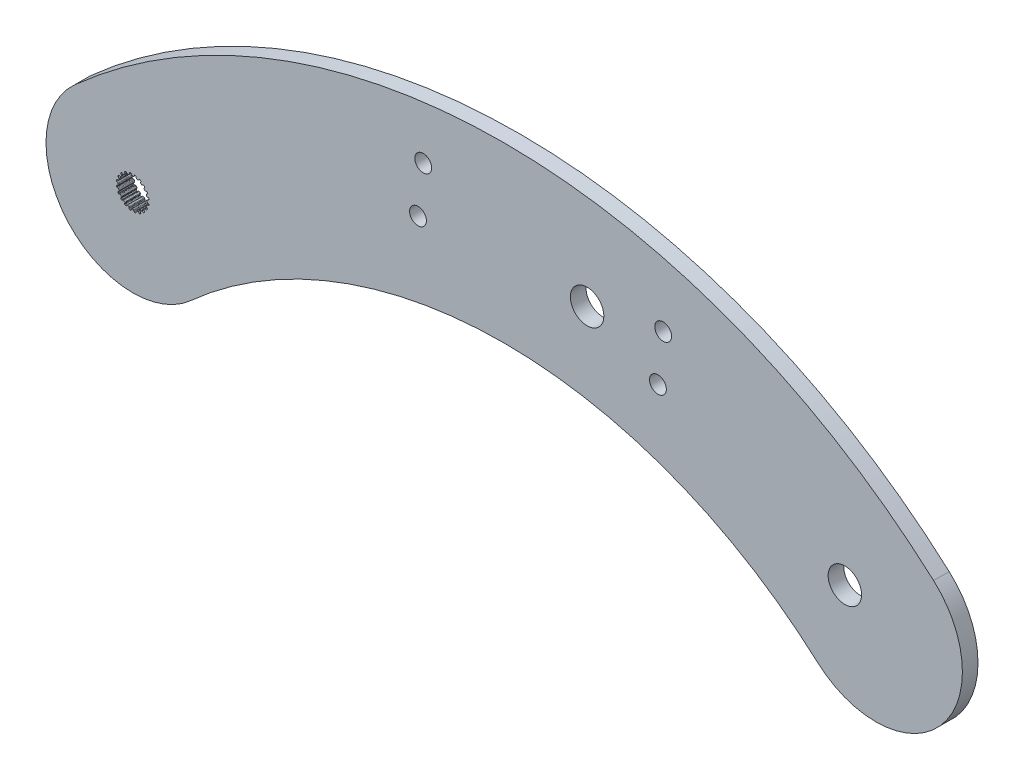
SolidWorks part; units mm, degrees
ref_plane "Front Plane" through (0, 0, 0) normal (0, 0, 1) x (1, 0, 0)
ref_plane "Top Plane" through (0, 0, 0) normal (0, 1, 0) x (1, 0, 0)
ref_plane "Right Plane" through (0, 0, 0) normal (1, 0, 0) x (0, 0, -1)
sketch "Sketch1" plane through (0, 0, 0) normal (0, 0, 1) x (1, 0, 0)
  line L0 (-0.1069, 2.9699) -> (0.1069, 2.9699)
  line L1 (0.3159, 3.2375) -> (0.2537, 3.0575)
  line L2 (-0.2964, 3.2367) -> (-0.2318, 3.0575)
  line L3 (-0.2964, 3.2367) -> (0.3159, 3.2375) construction
  line L4 (0, 3.3252) -> (0, 0) construction
  line L5 (-0.2318, 3.0575) -> (0.2537, 3.0575) construction
  line L6 (-0.4281, 3.3241) -> (0.4281, 3.3263) construction
  line L7 (0.7183, 3.1698) -> (0.7244, 2.9795)
  line L8 (0.816, 2.8576) -> (1.0195, 2.7915)
  line L9 (1.3009, 2.9815) -> (1.1862, 2.8295)
  line L10 (1.6627, 2.7927) -> (1.6097, 2.6099)
  line L11 (1.6591, 2.4655) -> (1.8322, 2.3398)
  line L12 (2.1585, 2.4335) -> (2.0025, 2.3245)
  line L13 (2.4443, 2.1423) -> (2.3374, 1.9847)
  line L14 (2.3398, 1.8322) -> (2.4655, 1.6591)
  line L15 (2.8049, 1.6474) -> (2.6228, 1.5919)
  line L16 (2.9866, 1.2821) -> (2.8363, 1.1653)
  line L17 (2.7915, 1.0195) -> (2.8576, 0.816)
  line L18 (3.1767, 0.7) -> (2.9863, 0.7035)
  line L19 (3.2367, 0.2964) -> (3.0575, 0.2318)
  line L20 (2.9699, 0.1069) -> (2.9699, -0.1069)
  line L21 (3.2375, -0.3159) -> (3.0575, -0.2537)
  line L22 (3.1698, -0.7183) -> (2.9795, -0.7244)
  line L23 (2.8576, -0.816) -> (2.7915, -1.0195)
  line L24 (2.9815, -1.3009) -> (2.8295, -1.1862)
  line L25 (2.7927, -1.6627) -> (2.6099, -1.6097)
  line L26 (2.4655, -1.6591) -> (2.3398, -1.8322)
  line L27 (2.4335, -2.1585) -> (2.3245, -2.0025)
  line L28 (2.1423, -2.4443) -> (1.9847, -2.3374)
  line L29 (1.8322, -2.3398) -> (1.6591, -2.4655)
  line L30 (1.6474, -2.8049) -> (1.5919, -2.6228)
  line L31 (1.2821, -2.9866) -> (1.1653, -2.8363)
  line L32 (1.0195, -2.7915) -> (0.816, -2.8576)
  line L33 (0.7, -3.1767) -> (0.7035, -2.9863)
  line L34 (0.2964, -3.2367) -> (0.2318, -3.0575)
  line L35 (0.1069, -2.9699) -> (-0.1069, -2.9699)
  line L36 (-0.3159, -3.2375) -> (-0.2537, -3.0575)
  line L37 (-0.7183, -3.1698) -> (-0.7244, -2.9795)
  line L38 (-0.816, -2.8576) -> (-1.0195, -2.7915)
  line L39 (-1.3009, -2.9815) -> (-1.1862, -2.8295)
  line L40 (-1.6627, -2.7927) -> (-1.6097, -2.6099)
  line L41 (-1.6591, -2.4655) -> (-1.8322, -2.3398)
  line L42 (-2.1585, -2.4335) -> (-2.0025, -2.3245)
  line L43 (-2.4443, -2.1423) -> (-2.3374, -1.9847)
  line L44 (-2.3398, -1.8322) -> (-2.4655, -1.6591)
  line L45 (-2.8049, -1.6474) -> (-2.6228, -1.5919)
  line L46 (-2.9866, -1.2821) -> (-2.8363, -1.1653)
  line L47 (-2.7915, -1.0195) -> (-2.8576, -0.816)
  line L48 (-3.1767, -0.7) -> (-2.9863, -0.7035)
  line L49 (-3.2367, -0.2964) -> (-3.0575, -0.2318)
  line L50 (-2.9699, -0.1069) -> (-2.9699, 0.1069)
  line L51 (-3.2375, 0.3159) -> (-3.0575, 0.2537)
  line L52 (-3.1698, 0.7183) -> (-2.9795, 0.7244)
  line L53 (-2.8576, 0.816) -> (-2.7915, 1.0195)
  line L54 (-2.9815, 1.3009) -> (-2.8295, 1.1862)
  line L55 (-2.7927, 1.6627) -> (-2.6099, 1.6097)
  line L56 (-2.4655, 1.6591) -> (-2.3398, 1.8322)
  line L57 (-2.4335, 2.1585) -> (-2.3245, 2.0025)
  line L58 (-2.1423, 2.4443) -> (-1.9847, 2.3374)
  line L59 (-1.8322, 2.3398) -> (-1.6591, 2.4655)
  line L60 (-1.6474, 2.8049) -> (-1.5919, 2.6228)
  line L61 (-1.2821, 2.9866) -> (-1.1653, 2.8363)
  line L62 (-1.0195, 2.7915) -> (-0.816, 2.8576)
  line L63 (-0.7, 3.1767) -> (-0.7035, 2.9863)
  line L64 (0.4281, 3.3263) -> (0.62, 3.2938)
  line L65 (1.4351, 3.0312) -> (1.6075, 2.9409)
  line L66 (2.3015, 2.4394) -> (2.4376, 2.3003)
  line L67 (2.9427, 1.6088) -> (3.0291, 1.4344)
  line L68 (3.2958, 0.6207) -> (3.3241, 0.4281)
  line L69 (3.3263, -0.4281) -> (3.2938, -0.62)
  line L70 (3.0312, -1.4351) -> (2.9409, -1.6075)
  line L71 (2.4394, -2.3015) -> (2.3003, -2.4376)
  line L72 (1.6088, -2.9427) -> (1.4344, -3.0291)
  line L73 (0.6207, -3.2958) -> (0.4281, -3.3241)
  line L74 (-0.4281, -3.3263) -> (-0.62, -3.2938)
  line L75 (-1.4351, -3.0312) -> (-1.6075, -2.9409)
  line L76 (-2.3015, -2.4394) -> (-2.4376, -2.3003)
  line L77 (-2.9427, -1.6088) -> (-3.0291, -1.4344)
  line L78 (-3.2958, -0.6207) -> (-3.3241, -0.4281)
  line L79 (-3.3263, 0.4281) -> (-3.2938, 0.62)
  line L80 (-3.0312, 1.4351) -> (-2.9409, 1.6075)
  line L81 (-2.4394, 2.3015) -> (-2.3003, 2.4376)
  line L82 (-1.6088, 2.9427) -> (-1.4344, 3.0291)
  line L83 (-0.6207, 3.2958) -> (-0.4281, 3.3241)
  line L84 (-11.8753, 13.2369) -> (11.8753, -13.2369) construction
  line L85 (164.2753, 13.2369) -> (140.5247, -13.2369) construction
  line L86 (0, 0) -> (152.4, 0) construction
  arc A0 (0.2537, 3.0575) -> (0.1069, 2.9699) centre (0.1283, 3.1009) cw
  arc A1 (-0.2318, 3.0575) -> (-0.1069, 2.9699) centre (-0.1069, 3.1026) ccw
  arc A2 (0.62, 3.2938) -> (0.7183, 3.1698) centre (0.5856, 3.1656) cw
  arc A3 (0.7244, 2.9795) -> (0.816, 2.8576) centre (0.857, 2.9838) ccw
  arc A4 (-0.4281, 3.3241) -> (-0.2964, 3.2367) centre (-0.4213, 3.1916) cw
  arc A5 (0.4281, 3.3263) -> (0.3159, 3.2375) centre (0.4413, 3.1942) ccw
  arc A6 (1.1862, 2.8295) -> (1.0195, 2.7915) centre (1.0802, 2.9095) cw
  arc A7 (1.4351, 3.0312) -> (1.3009, 2.9815) centre (1.4068, 2.9015) ccw
  arc A8 (1.6075, 2.9409) -> (1.6627, 2.7927) centre (1.5352, 2.8297) cw
  arc A9 (1.6097, 2.6099) -> (1.6591, 2.4655) centre (1.7371, 2.5729) ccw
  arc A10 (2.0025, 2.3245) -> (1.8322, 2.3398) centre (1.9264, 2.4332) cw
  arc A11 (2.3015, 2.4394) -> (2.1585, 2.4335) centre (2.2346, 2.3248) ccw
  arc A12 (2.4376, 2.3003) -> (2.4443, 2.1423) centre (2.3345, 2.2168) cw
  arc A13 (2.3374, 1.9847) -> (2.3398, 1.8322) centre (2.4472, 1.9102) ccw
  arc A14 (2.6228, 1.5919) -> (2.4655, 1.6591) centre (2.5841, 1.7189) cw
  arc A15 (2.9427, 1.6088) -> (2.8049, 1.6474) centre (2.8436, 1.5205) ccw
  arc A16 (3.0291, 1.4344) -> (2.9866, 1.2821) centre (2.9052, 1.3869) cw
  arc A17 (2.8363, 1.1653) -> (2.7915, 1.0195) centre (2.9177, 1.0605) ccw
  arc A18 (2.9863, 0.7035) -> (2.8576, 0.816) centre (2.9887, 0.8362) cw
  arc A19 (3.2958, 0.6207) -> (3.1767, 0.7) centre (3.1743, 0.5673) ccw
  arc A20 (3.3241, 0.4281) -> (3.2367, 0.2964) centre (3.1916, 0.4213) cw
  arc A21 (3.0575, 0.2318) -> (2.9699, 0.1069) centre (3.1026, 0.1069) ccw
  arc A22 (3.0575, -0.2537) -> (2.9699, -0.1069) centre (3.1009, -0.1283) cw
  arc A23 (3.3263, -0.4281) -> (3.2375, -0.3159) centre (3.1942, -0.4413) ccw
  arc A24 (3.2938, -0.62) -> (3.1698, -0.7183) centre (3.1656, -0.5856) cw
  arc A25 (2.9795, -0.7244) -> (2.8576, -0.816) centre (2.9838, -0.857) ccw
  arc A26 (2.8295, -1.1862) -> (2.7915, -1.0195) centre (2.9095, -1.0802) cw
  arc A27 (3.0312, -1.4351) -> (2.9815, -1.3009) centre (2.9015, -1.4068) ccw
  arc A28 (2.9409, -1.6075) -> (2.7927, -1.6627) centre (2.8297, -1.5352) cw
  arc A29 (2.6099, -1.6097) -> (2.4655, -1.6591) centre (2.5729, -1.7371) ccw
  arc A30 (2.3245, -2.0025) -> (2.3398, -1.8322) centre (2.4332, -1.9264) cw
  arc A31 (2.4394, -2.3015) -> (2.4335, -2.1585) centre (2.3248, -2.2346) ccw
  arc A32 (2.3003, -2.4376) -> (2.1423, -2.4443) centre (2.2168, -2.3345) cw
  arc A33 (1.9847, -2.3374) -> (1.8322, -2.3398) centre (1.9102, -2.4472) ccw
  arc A34 (1.5919, -2.6228) -> (1.6591, -2.4655) centre (1.7189, -2.5841) cw
  arc A35 (1.6088, -2.9427) -> (1.6474, -2.8049) centre (1.5205, -2.8436) ccw
  arc A36 (1.4344, -3.0291) -> (1.2821, -2.9866) centre (1.3869, -2.9052) cw
  arc A37 (1.1653, -2.8363) -> (1.0195, -2.7915) centre (1.0605, -2.9177) ccw
  arc A38 (0.7035, -2.9863) -> (0.816, -2.8576) centre (0.8362, -2.9887) cw
  arc A39 (0.6207, -3.2958) -> (0.7, -3.1767) centre (0.5673, -3.1743) ccw
  arc A40 (0.4281, -3.3241) -> (0.2964, -3.2367) centre (0.4213, -3.1916) cw
  arc A41 (0.2318, -3.0575) -> (0.1069, -2.9699) centre (0.1069, -3.1026) ccw
  arc A42 (-0.2537, -3.0575) -> (-0.1069, -2.9699) centre (-0.1283, -3.1009) cw
  arc A43 (-0.4281, -3.3263) -> (-0.3159, -3.2375) centre (-0.4413, -3.1942) ccw
  arc A44 (-0.62, -3.2938) -> (-0.7183, -3.1698) centre (-0.5856, -3.1656) cw
  arc A45 (-0.7244, -2.9795) -> (-0.816, -2.8576) centre (-0.857, -2.9838) ccw
  arc A46 (-1.1862, -2.8295) -> (-1.0195, -2.7915) centre (-1.0802, -2.9095) cw
  arc A47 (-1.4351, -3.0312) -> (-1.3009, -2.9815) centre (-1.4068, -2.9015) ccw
  arc A48 (-1.6075, -2.9409) -> (-1.6627, -2.7927) centre (-1.5352, -2.8297) cw
  arc A49 (-1.6097, -2.6099) -> (-1.6591, -2.4655) centre (-1.7371, -2.5729) ccw
  arc A50 (-2.0025, -2.3245) -> (-1.8322, -2.3398) centre (-1.9264, -2.4332) cw
  arc A51 (-2.3015, -2.4394) -> (-2.1585, -2.4335) centre (-2.2346, -2.3248) ccw
  arc A52 (-2.4376, -2.3003) -> (-2.4443, -2.1423) centre (-2.3345, -2.2168) cw
  arc A53 (-2.3374, -1.9847) -> (-2.3398, -1.8322) centre (-2.4472, -1.9102) ccw
  arc A54 (-2.6228, -1.5919) -> (-2.4655, -1.6591) centre (-2.5841, -1.7189) cw
  arc A55 (-2.9427, -1.6088) -> (-2.8049, -1.6474) centre (-2.8436, -1.5205) ccw
  arc A56 (-3.0291, -1.4344) -> (-2.9866, -1.2821) centre (-2.9052, -1.3869) cw
  arc A57 (-2.8363, -1.1653) -> (-2.7915, -1.0195) centre (-2.9177, -1.0605) ccw
  arc A58 (-2.9863, -0.7035) -> (-2.8576, -0.816) centre (-2.9887, -0.8362) cw
  arc A59 (-3.2958, -0.6207) -> (-3.1767, -0.7) centre (-3.1743, -0.5673) ccw
  arc A60 (-3.3241, -0.4281) -> (-3.2367, -0.2964) centre (-3.1916, -0.4213) cw
  arc A61 (-3.0575, -0.2318) -> (-2.9699, -0.1069) centre (-3.1026, -0.1069) ccw
  arc A62 (-3.0575, 0.2537) -> (-2.9699, 0.1069) centre (-3.1009, 0.1283) cw
  arc A63 (-3.3263, 0.4281) -> (-3.2375, 0.3159) centre (-3.1942, 0.4413) ccw
  arc A64 (-3.2938, 0.62) -> (-3.1698, 0.7183) centre (-3.1656, 0.5856) cw
  arc A65 (-2.9795, 0.7244) -> (-2.8576, 0.816) centre (-2.9838, 0.857) ccw
  arc A66 (-2.8295, 1.1862) -> (-2.7915, 1.0195) centre (-2.9095, 1.0802) cw
  arc A67 (-3.0312, 1.4351) -> (-2.9815, 1.3009) centre (-2.9015, 1.4068) ccw
  arc A68 (-2.9409, 1.6075) -> (-2.7927, 1.6627) centre (-2.8297, 1.5352) cw
  arc A69 (-2.6099, 1.6097) -> (-2.4655, 1.6591) centre (-2.5729, 1.7371) ccw
  arc A70 (-2.3245, 2.0025) -> (-2.3398, 1.8322) centre (-2.4332, 1.9264) cw
  arc A71 (-2.4394, 2.3015) -> (-2.4335, 2.1585) centre (-2.3248, 2.2346) ccw
  arc A72 (-2.3003, 2.4376) -> (-2.1423, 2.4443) centre (-2.2168, 2.3345) cw
  arc A73 (-1.9847, 2.3374) -> (-1.8322, 2.3398) centre (-1.9102, 2.4472) ccw
  arc A74 (-1.5919, 2.6228) -> (-1.6591, 2.4655) centre (-1.7189, 2.5841) cw
  arc A75 (-1.6088, 2.9427) -> (-1.6474, 2.8049) centre (-1.5205, 2.8436) ccw
  arc A76 (-1.4344, 3.0291) -> (-1.2821, 2.9866) centre (-1.3869, 2.9052) cw
  arc A77 (-1.1653, 2.8363) -> (-1.0195, 2.7915) centre (-1.0605, 2.9177) ccw
  arc A78 (-0.7035, 2.9863) -> (-0.816, 2.8576) centre (-0.8362, 2.9887) cw
  arc A79 (-0.6207, 3.2958) -> (-0.7, 3.1767) centre (-0.5673, 3.1743) ccw
  circle A80 centre (0, 0) radius 12.7 construction
  arc A81 (-11.8753, 13.2369) -> (164.2753, 13.2369) centre (76.2, -84.9368) cw
  arc A82 (11.8753, -13.2369) -> (140.5247, -13.2369) centre (76.2, -84.9368) cw
  arc A84 (-11.8753, 13.2369) -> (11.8753, -13.2369) centre (0, 0) ccw
  arc A85 (164.2753, 13.2369) -> (140.5247, -13.2369) centre (152.4, 0) cw
  point P14 (0, 2.9699)
  point P26 (0, 0)
  point P247 (0, 0)
  dimension "D4" = 0.1327
  dimension "D8" = 20
  dimension "D9" = 25.4
  dimension "D10" = 131.8914
  dimension "D1" = 2.9699
  dimension "D2" = 0.2139
  dimension "D3" = 0.1904
  dimension "D5" = 0.0877
  dimension "D6" = 0.4855
  dimension "D7" = 0.8563
  dimension "D11" = 35.5662
  dimension "D12" = 152.4
extrude "Boss-Extrude1" add sketch "Sketch1" along normal blind 3.2004
sketch "Sketch2" plane through (0, 0, 3.2004) normal (0, 0, 1) x (1, 0, 0)
  line L0 (93.2069, 26.3935) -> (93.3668, 27.8728) construction
  line L5 (146.0724, 3.3152) -> (146.6487, 4.1197) construction
  line L7 (164.2753, 13.2369) -> (140.5247, -13.2369) construction
  line L13 (146.6487, 4.1197) -> (152.4, 0) construction
  line L19 (58.5184, 25.1155) -> (59.5935, 35.0576) construction
  line L20 (107.7315, 19.7937) -> (108.8066, 29.7357) construction
  line L24 (59.056, 30.0865) -> (108.2691, 24.7647) construction
  circle A7 centre (59.5935, 35.0576) radius 1.7272
  circle A9 centre (107.7315, 19.7937) radius 1.7272
  circle A10 centre (108.8066, 29.7357) radius 1.7272
  circle A11 centre (58.5184, 25.1155) radius 1.7272
  circle A13 centre (93.2069, 26.3935) radius 3.429
  arc A14 (0, 0) -> (152.4, 0) centre (76.2, -84.9368) cw construction
  arc A15 (-11.8753, 13.2369) -> (11.8753, -13.2369) centre (0, 0) ccw construction
  arc A16 (140.5247, -13.2369) -> (164.2753, 13.2369) centre (152.4, 0) ccw construction
  arc A17 (164.2753, 13.2369) -> (-11.8753, 13.2369) centre (76.2, -84.9368) ccw construction
  circle A18 centre (146.0724, 3.3152) radius 3.429
  point P0 (93.2069, 26.3935)
  point P19 (58.8129, 27.839)
  point P25 (49.1481, 25.9185)
  point P26 (58.8129, 27.839)
  point P27 (0, 0)
  point P28 (0, 0)
  point P30 (0, 0)
  dimension "D2" = 15.15
  dimension "D3" = 6.858
  dimension "D5" = 3.4544
  dimension "D10" = 96.282
  dimension "D6" = 2.2606
  dimension "D8" = 7.0746
  dimension "D11" = 6.858
  dimension "D1" = 49.5
  dimension "D4" = 10
  dimension "D7" = 1.4879
  dimension "D9" = 0.9896
extrude "Cut-Extrude1" cut sketch "Sketch2" against normal up to surface (3.2004 mm away) up to face at (76.2, 8.6481, 0)
